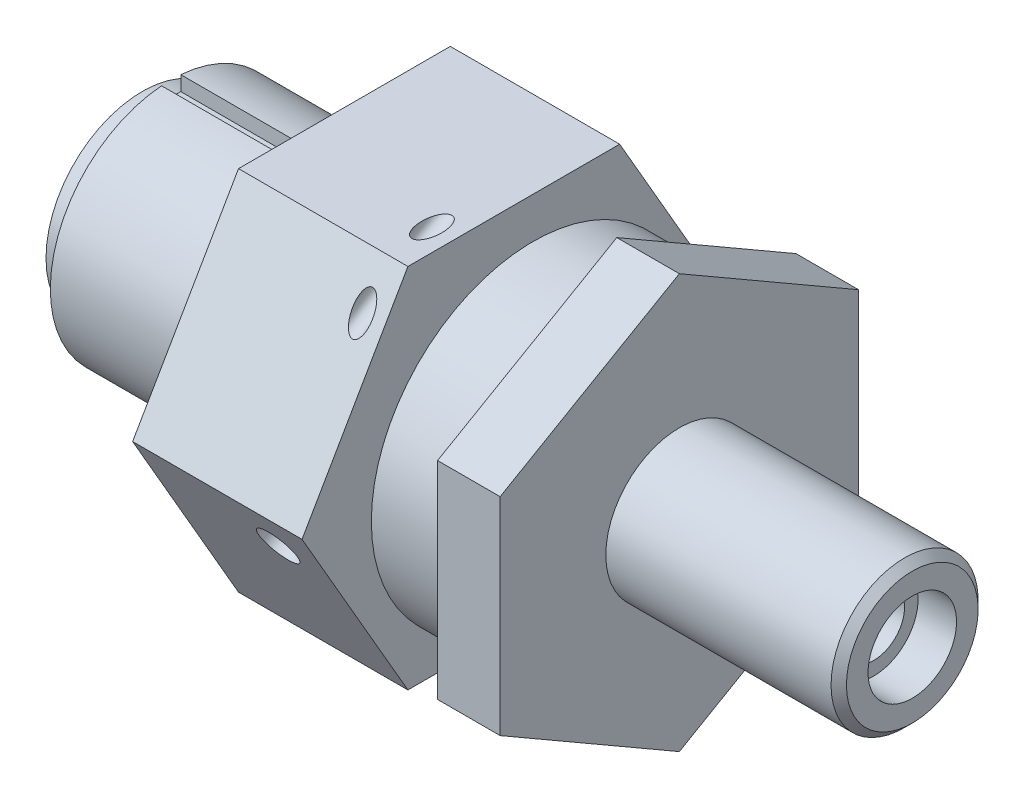
SolidWorks part; units mm, degrees
ref_plane "Front Plane" through (0, 0, 0) normal (0, 0, 1) x (1, 0, 0)
ref_plane "Top Plane" through (0, 0, 0) normal (0, 1, 0) x (1, 0, 0)
ref_plane "Right Plane" through (0, 0, 0) normal (1, 0, 0) x (0, 0, -1)
sketch "Sketch1" plane through (0, 0, 0) normal (0, 0, 1) x (1, 0, 0)
  line L0 (0, 0) -> (119.471, 0) construction
  line L1 (0, 0) -> (0, 5)
  line L2 (0, 5) -> (1.5, 5)
  line L3 (1.5, 5) -> (1.5, 6.275)
  line L4 (1.5, 6.275) -> (11, 6.275)
  line L5 (11, 6.275) -> (11, 8.75)
  line L6 (11, 8.75) -> (10.5, 8.75)
  line L7 (10.5, 8.75) -> (10.5, 11)
  line L8 (10.5, 11) -> (19.3, 11)
  line L9 (19.3, 11) -> (19.3, 6.5)
  line L10 (19.3, 6.5) -> (20.3, 6.5)
  line L11 (20.3, 6.5) -> (20.3, 8.4)
  line L12 (20.3, 8.4) -> (24.65, 8.4)
  line L13 (24.65, 8.4) -> (24.65, 10.75)
  line L14 (24.65, 10.75) -> (27.9, 10.75)
  line L15 (27.9, 10.75) -> (27.9, 3.82)
  line L16 (27.9, 3.82) -> (40, 3.82)
  line L17 (40, 3.82) -> (40, 2.3)
  line L18 (40, 2.3) -> (38, 2.3)
  line L19 (38, 2.3) -> (38, 1.6)
  line L20 (38, 1.6) -> (12, 1.6)
  line L21 (12, 1.6) -> (12, 0)
  line L22 (0, 0) -> (12, 0)
  dimension "D1" = 10
  dimension "D2" = 12.55
  dimension "D3" = 1.5
  dimension "D4" = 10.5
  dimension "D5" = 0.5
  dimension "D6" = 17.5
  dimension "D7" = 22
  dimension "D8" = 1
  dimension "D9" = 13
  dimension "D10" = 16.8
  dimension "D11" = 21.5
  dimension "D12" = 2
  dimension "D13" = 4.6
  dimension "D14" = 7.64
  dimension "D15" = 3.2
  dimension "D16" = 8.8
  dimension "D17" = 7.6
  dimension "D18" = 3.25
  dimension "D19" = 40
  dimension "D20" = 28
revolve "Revolve1" add sketch "Sketch1" angle 360 about L0
cosmetic thread "Cosmetic Thread1" parameters "D2"=12
cosmetic thread "Cosmetic Thread2" parameters "D2"=6.64
chamfer "Chamfer1" distance 0.4 angle 45 1 edges at (40, 0, 3.82)
sketch "Sketch2" plane through (27.9, 0, 0) normal (1, 0, 0) x (0, 0, -1)
  line L1 (0, 10.75) -> (-9.3098, 5.375)
  line L2 (-9.3098, 5.375) -> (-9.3098, -5.375)
  line L3 (-9.3098, -5.375) -> (0, -10.75)
  line L4 (0, -10.75) -> (9.3098, -5.375)
  line L5 (9.3098, -5.375) -> (9.3098, 5.375)
  line L6 (9.3098, 5.375) -> (0, 10.75)
  circle A0 centre (0, 0) radius 9.3098 construction
  circle A1 centre (0, 0) radius 10.75 construction
  circle A3 centre (0, 0) radius 11.9257
  dimension "D1" = 23.8515
extrude "Extrude1" cut sketch "Sketch2" against normal up to next
sketch "Sketch3" plane through (19.3, 0, 0) normal (1, 0, 0) x (0, 0, -1)
  line L1 (-5.5, 9.5263) -> (-11, 0)
  line L2 (-11, 0) -> (-5.5, -9.5263)
  line L3 (-5.5, -9.5263) -> (5.5, -9.5263)
  line L4 (5.5, -9.5263) -> (11, 0)
  line L5 (11, 0) -> (5.5, 9.5263)
  line L6 (5.5, 9.5263) -> (-5.5, 9.5263)
  circle A0 centre (0, 0) radius 9.5263 construction
  circle A1 centre (0, 0) radius 11 construction
  circle A2 centre (0, 0) radius 13.4912
  dimension "D1" = 26.9823
extrude "Extrude2" cut sketch "Sketch3" against normal up to next
sketch "Sketch4" plane through (1.5, 0, 0) normal (-1, 0, 0) x (0, 0, 1)
  line L0 (0, 0) -> (0, 10.75) construction
  line L1 (-0.5, 6.6358) -> (0.5, 6.6358)
  line L2 (-0.5, 6.6358) -> (-0.5, 5.4912)
  line L3 (-0.5, 5.4912) -> (0.5, 5.4912)
  line L4 (0.5, 6.6358) -> (0.5, 5.4912)
  line L5 (0, 10.75) -> (-9.3098, 5.375) construction
  dimension "D1" = 1
  dimension "D2" = 5.4912
extrude "Extrude3" cut sketch "Sketch4" against normal up to surface (9.5 mm away) up to face at (11, 0, 6.275)
sketch "Sketch5" plane through (0, -4.7631, 8.25) normal (0, -0.5, 0.866) x (1, 0, 0)
  line L0 (19.3, 11) -> (19.3, 5.5) construction
  circle A0 centre (18.146, 9.8) radius 0.5207
  dimension "D1" = 1.0414
  dimension "D2" = 1.154
  dimension "D3" = 9.8
extrude "Cut-Extrude1" cut sketch "Sketch5" against normal through all both and the other way through all
sketch "Sketch6" plane through (0, -4.7631, 8.25) normal (0, -0.5, 0.866) x (1, 0, 0)
  circle A0 centre (16.8087, 2.9941) radius 1.016
extrude "Cut-Extrude2" cut sketch "Sketch6" against normal blind 0.5
sketch "Sketch7" plane through (0, 4.7631, -8.25) normal (0, 0.5, -0.866) x (-1, 0, 0)
  circle A1 centre (-16.8087, 2.9941) radius 1.016
  circle A2 centre (-16.8087, 2.9941) radius 1.016
  dimension "D1" = 0
extrude "Cut-Extrude3" cut sketch "Sketch7" against normal blind 0.5
